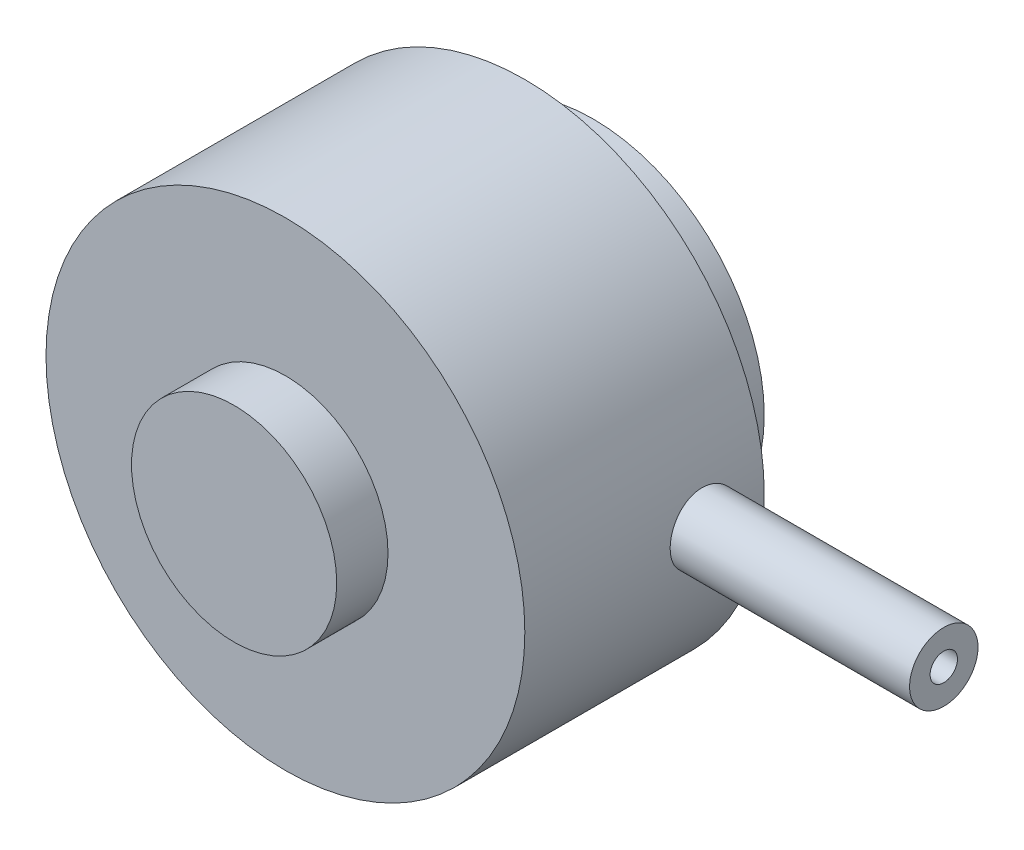
SolidWorks part; units mm, degrees
ref_plane "Front Plane" through (0, 0, 0) normal (0, 0, 1) x (1, 0, 0)
ref_plane "Top Plane" through (0, 0, 0) normal (0, 1, 0) x (1, 0, 0)
ref_plane "Right Plane" through (0, 0, 0) normal (1, 0, 0) x (0, 0, -1)
sketch "Sketch1" plane through (0, 0, 0) normal (0, 0, 1) x (1, 0, 0)
  circle A0 centre (0, 0) radius 5
  dimension "D1" = 10
extrude "Boss-Extrude1" add sketch "Sketch1" along normal blind 2
sketch "Sketch2" plane through (0, 0, 2) normal (0, 0, 1) x (1, 0, 0)
  circle A0 centre (0, 0) radius 7
  dimension "D1" = 14
extrude "Boss-Extrude2" add sketch "Sketch2" along normal blind 7
sketch "Sketch3" plane through (0, 0, 9) normal (0, 0, 1) x (1, 0, 0)
  circle A0 centre (0, 0) radius 3
  dimension "D1" = 6
extrude "Boss-Extrude3" add sketch "Sketch3" along normal blind 1.5
ref_plane "Plane4" through (6, 0, 0) normal (1, 0, 0) x (0, 0, -1)
sketch "Sketch4" plane through (6, 0, 0) normal (1, 0, 0) x (0, 0, -1)
  circle A0 centre (-3.75, 0) radius 1
  point P2 (-3.3302, -1.724)
  dimension "D1" = 2
  dimension "D2" = 3.75
extrude "Boss-Extrude4" add sketch "Sketch4" along normal blind 8
sketch "Sketch5" plane through (14, 0, 0) normal (1, 0, 0) x (0, 0, -1)
  circle A0 centre (-3.75, 0) radius 0.4
  circle A1 centre (-3.75, 0) radius 1 construction
  point P2 (0, 0)
  dimension "D1" = 0.8
extrude "Cut-Extrude1" cut sketch "Sketch5" against normal blind 8
sketch "Sketch7" plane through (0, 0, 0) normal (0, 0, -1) x (-1, 0, 0)
  circle A0 centre (0, 0) radius 0.35
  circle A1 centre (0, 2) radius 0.35
  circle A2 centre (0, -2) radius 0.35
  circle A3 centre (2, 0) radius 0.35
  circle A4 centre (2, 2) radius 0.35
  circle A5 centre (2, -2) radius 0.35
  circle A6 centre (-2, 0) radius 0.35
  circle A7 centre (-2, 2) radius 0.35
  circle A8 centre (-2, -2) radius 0.35
  point P7 (0, 0)
  dimension "D1" = 0.7
  dimension "D2" = 2
  dimension "D3" = 2
  dimension "D6" = 2
  dimension "D7" = 2
  dimension "D4" = 2
  dimension "D5" = 2
extrude "Cut-Extrude2" cut sketch "Sketch7" against normal blind 0.4
